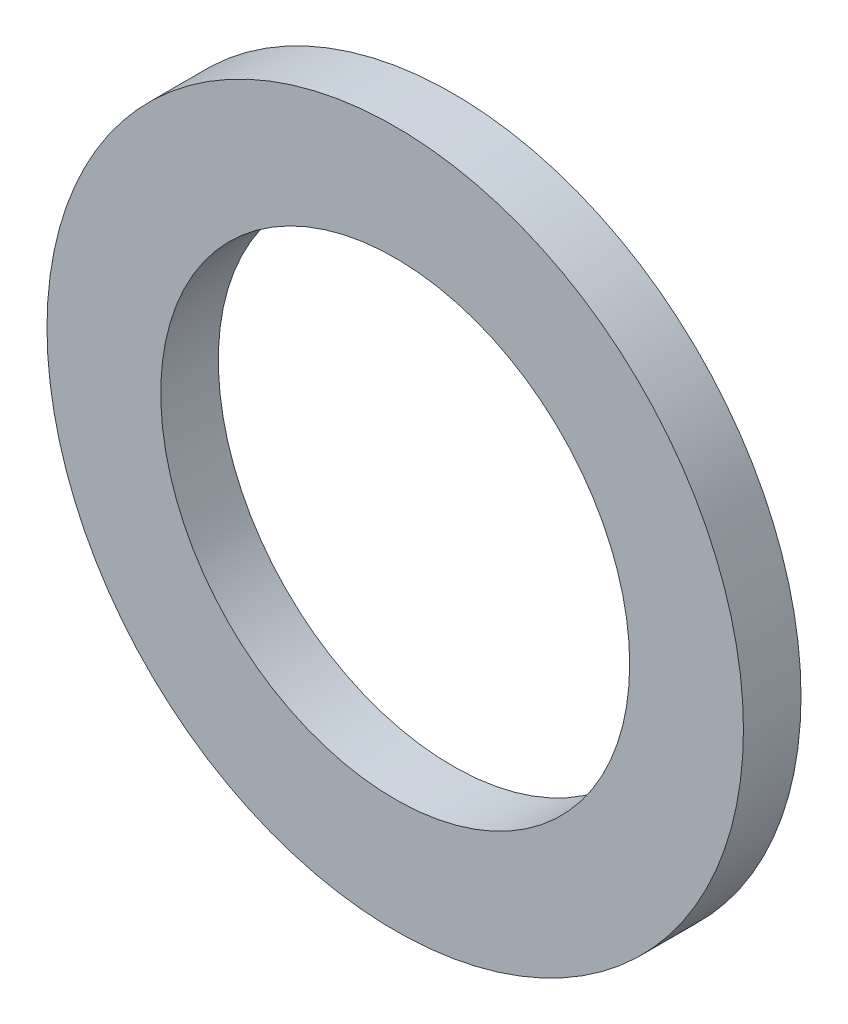
SolidWorks part; units mm, degrees
material "Nylon 101"
ref_plane "Front" through (0, 0, 0) normal (0, 0, 1) x (1, 0, 0)
ref_plane "Top" through (0, 0, 0) normal (0, 1, 0) x (1, 0, 0)
ref_plane "Right" through (0, 0, 0) normal (1, 0, 0) x (0, 0, -1)
sketch "Sketch1" plane through (0, 0, 0) normal (0, 0, 1) x (1, 0, 0)
  circle A0 centre (0, 0) radius 6.4135
  circle A1 centre (0, 0) radius 9.525
  dimension "D1" = 19.05
  dimension "D2" = 12.827
extrude "Boss-Extrude1" add sketch "Sketch1" along normal blind 1.5748
